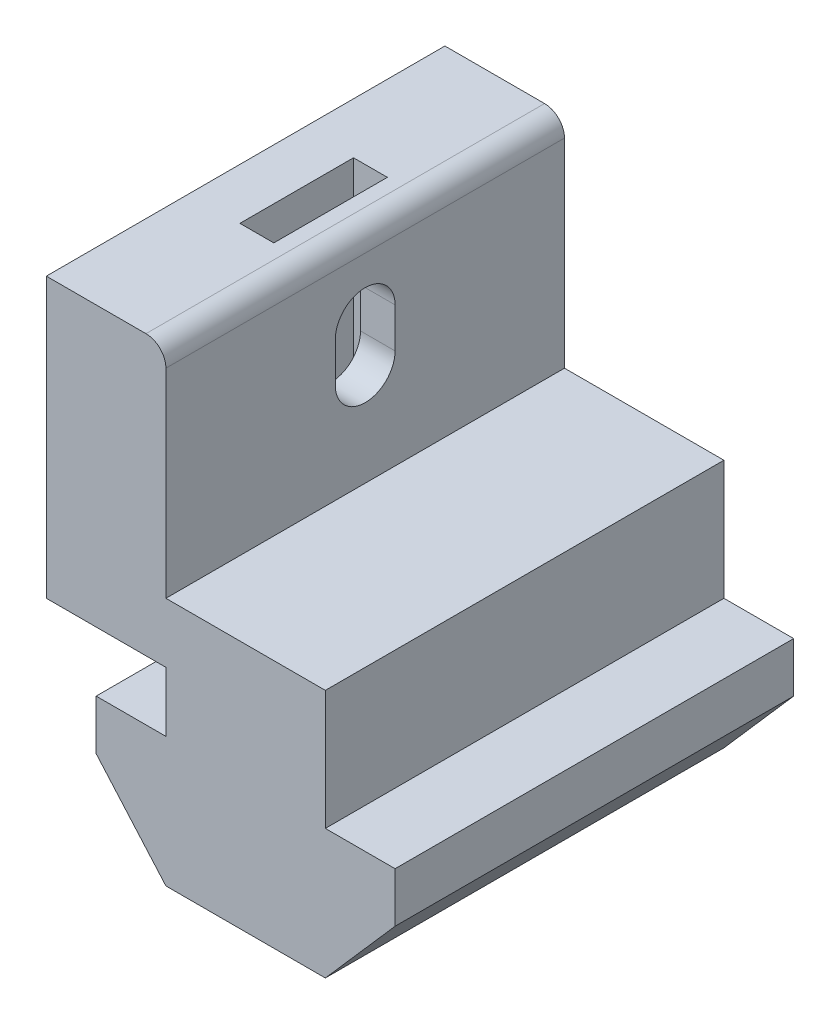
SolidWorks part; units mm, degrees
ref_plane "Piano frontale" through (0, 0, 0) normal (0, 0, 1) x (1, 0, 0)
ref_plane "Piano superiore" through (0, 0, 0) normal (0, 1, 0) x (1, 0, 0)
ref_plane "Piano destro" through (0, 0, 0) normal (1, 0, 0) x (0, 0, -1)
sketch "Schizzo2" plane through (0, 0, 0) normal (0, 0, 1) x (1, 0, 0)
  line L0 (0, 0) -> (0, 12.9875) construction
  line L1 (-4, 9.5) -> (-10, 9.5)
  line L2 (-10, 9.5) -> (-10, 23.5)
  line L3 (-10, 23.5) -> (-5, 23.5)
  line L4 (-4, 22.5) -> (-4, 12.5)
  line L5 (-4, 12.5) -> (4, 12.5)
  line L6 (4, 12.5) -> (4, 9.5)
  line L13 (-4, 0) -> (4, 0)
  line L14 (-7.5, 4) -> (-4, 0)
  line L15 (-7.5, 6.5) -> (-7.5, 4)
  line L16 (-4, 6.5) -> (-7.5, 6.5)
  line L17 (-4, 9.5) -> (-4, 6.5)
  line L44 (7.5, 4) -> (4, 0)
  line L45 (7.5, 6.5) -> (7.5, 4)
  line L46 (4, 6.5) -> (7.5, 6.5)
  line L72 (4, 9.5) -> (4, 6.5)
  arc A0 (-5, 23.5) -> (-4, 22.5) centre (-5, 22.5) cw
  point P9 (-4, 23.5)
  dimension "D11" = 1
  dimension "D1" = 8
  dimension "D2" = 4
  dimension "D3" = 2.5
  dimension "D4" = 8
  dimension "D5" = 3
  dimension "D6" = 15
  dimension "D7" = 10
  dimension "D8" = 6
  dimension "D9" = 3
  dimension "D10" = 14
extrude "Estrusione-Estrusione1" add sketch "Schizzo2" against normal blind 20
sketch "Schizzo6" plane through (-10, 0, 0) normal (-1, 0, 0) x (0, 0, 1)
  line L0 (0, 23.5) -> (0, 9.5) construction
  line L1 (-20, 23.5) -> (0, 23.5) construction
  line L2 (-10, 19.5) -> (-10, 17.5) construction
  line L3 (-8.5, 19.5) -> (-8.5, 17.5)
  line L4 (-11.5, 19.5) -> (-11.5, 17.5)
  line L5 (-20, 9.5) -> (0, 9.5) construction
  arc A1 (-8.5, 19.5) -> (-11.5, 19.5) centre (-10, 19.5) ccw
  arc A2 (-11.5, 17.5) -> (-8.5, 17.5) centre (-10, 17.5) ccw
  point P6 (-10, 18.5)
  dimension "D2" = 1.5
  dimension "D1" = 10
  dimension "D3" = 4
  dimension "D4" = 2
  dimension "D5" = 9
extrude "Taglio-Estrusione1" cut sketch "Schizzo6" against normal up to next
sketch "Schizzo11" plane through (0, 0, -20) normal (0, 0, -1) x (-1, 0, 0)
  line L0 (4, 0) -> (-4, 0) construction
  line L1 (7.5, 6.5) -> (7.5, 4) construction
  text T0 "4" font "Century Gothic" height 6.5
  dimension "D1" = 1
  dimension "D2" = 10.5
extrude "Estrusione-Estrusione4" add sketch "Schizzo11" along normal blind 0.6
sketch "Schizzo12" plane through (0, 23.5, 0) normal (0, 1, 0) x (1, 0, 0)
  line L0 (-5, 10) -> (-10, 10) construction
  line L1 (-5, 20) -> (-5, 0) construction
  line L2 (-10, 20) -> (-10, 0) construction
  line L4 (-5.7364, 7.15) -> (-7.4364, 7.15)
  line L5 (-5.7364, 7.15) -> (-5.7364, 12.85)
  line L6 (-5.7364, 12.85) -> (-7.4364, 12.85)
  line L7 (-7.4364, 7.15) -> (-7.4364, 12.85)
  line L8 (-5.7364, 7.15) -> (-7.4364, 12.85) construction
  line L9 (-5.7364, 12.85) -> (-7.4364, 7.15) construction
  point P6 (-6.5864, 10)
  dimension "D1" = 1.7
  dimension "D2" = 5.7
extrude "Taglio-Estrusione2" cut sketch "Schizzo12" against normal blind 10
